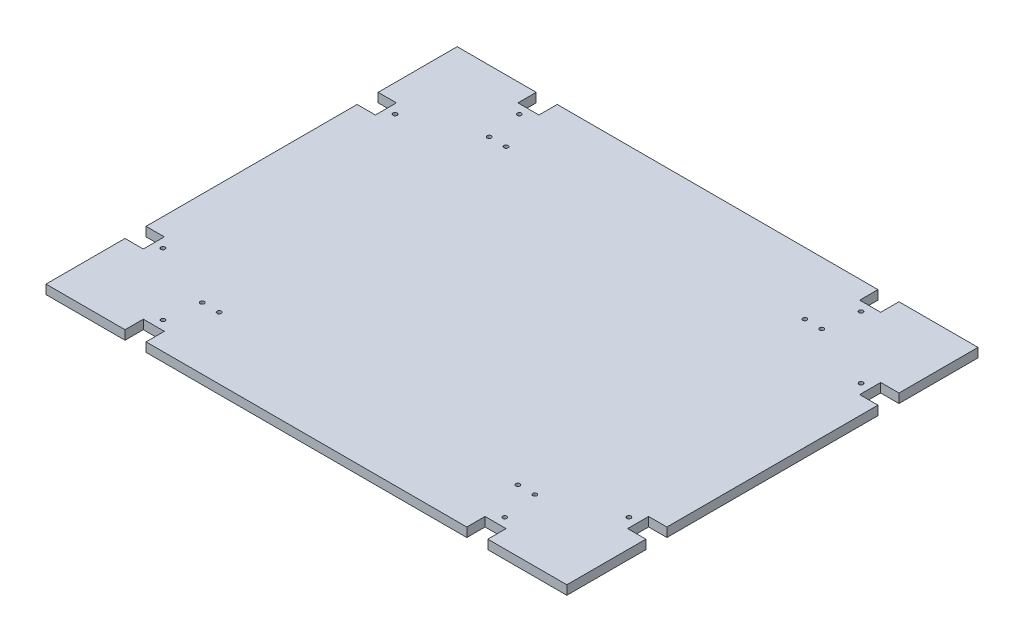
SolidWorks part; units mm, degrees
material "Multistrato di pioppo"
ref_plane "Piano frontale" through (0, 0, 0) normal (0, 0, 1) x (1, 0, 0)
ref_plane "Piano superiore" through (0, 0, 0) normal (0, 1, 0) x (1, 0, 0)
ref_plane "Piano destro" through (0, 0, 0) normal (1, 0, 0) x (0, 0, -1)
sketch "Schizzo1" plane through (0, 0, 0) normal (0, 1, 0) x (1, 0, 0)
  line L1 (0, 0) -> (-570, 0)
  line L2 (0, 0) -> (0, 450)
  line L3 (0, 450) -> (-570, 450)
  line L4 (-570, 0) -> (-570, 450)
  dimension "D1" = 570
  dimension "D2" = 450
extrude "Estrusione-Estrusione1" add sketch "Schizzo1" along normal blind 10
sketch "Schizzo2" plane through (0, 0, 0) normal (0, -1, 0) x (1, 0, 0)
  line L0 (-570, 0) -> (0, 0) construction
  line L1 (-483.5, 0) -> (-460.5, 0)
  line L3 (-483.5, 0) -> (-483.5, -20)
  line L5 (-483.5, -20) -> (-460.5, -20)
  line L6 (-460.5, 0) -> (-460.5, -20)
  line L7 (-483.5, 0) -> (-460.5, -20) construction
  line L8 (-483.5, -20) -> (-460.5, 0) construction
  line L9 (0, 0) -> (0, -450) construction
  line L10 (-109.5, 0) -> (-86.5, 0)
  line L11 (-109.5, 0) -> (-109.5, -20)
  line L12 (-109.5, -20) -> (-86.5, -20)
  line L13 (-86.5, 0) -> (-86.5, -20)
  line L14 (-109.5, 0) -> (-86.5, -20) construction
  line L15 (-109.5, -20) -> (-86.5, 0) construction
  line L16 (0, -86.5) -> (-20, -86.5)
  line L17 (0, -86.5) -> (0, -109.5)
  line L18 (0, -109.5) -> (-20, -109.5)
  line L19 (-20, -86.5) -> (-20, -109.5)
  line L20 (0, -86.5) -> (-20, -109.5) construction
  line L21 (0, -109.5) -> (-20, -86.5) construction
  line L22 (0, -450) -> (-570, -450) construction
  line L23 (0, -340.5) -> (-20, -340.5)
  line L24 (0, -340.5) -> (0, -363.5)
  line L25 (0, -363.5) -> (-20, -363.5)
  line L26 (-20, -340.5) -> (-20, -363.5)
  line L27 (0, -340.5) -> (-20, -363.5) construction
  line L28 (0, -363.5) -> (-20, -340.5) construction
  line L29 (-86.5, -450) -> (-109.5, -450)
  line L30 (-86.5, -450) -> (-86.5, -430)
  line L31 (-86.5, -430) -> (-109.5, -430)
  line L32 (-109.5, -450) -> (-109.5, -430)
  line L33 (-86.5, -450) -> (-109.5, -430) construction
  line L34 (-86.5, -430) -> (-109.5, -450) construction
  line L35 (-570, -450) -> (-570, 0) construction
  line L36 (-460.5, -450) -> (-483.5, -450)
  line L37 (-460.5, -450) -> (-460.5, -430)
  line L38 (-460.5, -430) -> (-483.5, -430)
  line L39 (-483.5, -450) -> (-483.5, -430)
  line L40 (-460.5, -450) -> (-483.5, -430) construction
  line L41 (-460.5, -430) -> (-483.5, -450) construction
  line L42 (-570, -363.5) -> (-550, -363.5)
  line L43 (-570, -363.5) -> (-570, -340.5)
  line L44 (-570, -340.5) -> (-550, -340.5)
  line L45 (-550, -363.5) -> (-550, -340.5)
  line L46 (-570, -363.5) -> (-550, -340.5) construction
  line L47 (-570, -340.5) -> (-550, -363.5) construction
  line L48 (-560, -98) -> (-10, -98) construction
  line L49 (-570, -109.5) -> (-550, -109.5)
  line L50 (-570, -109.5) -> (-570, -86.5)
  line L51 (-570, -86.5) -> (-550, -86.5)
  line L52 (-550, -109.5) -> (-550, -86.5)
  line L53 (-570, -109.5) -> (-550, -86.5) construction
  line L54 (-570, -86.5) -> (-550, -109.5) construction
  line L55 (-472, -10) -> (-472, -440) construction
  line L56 (-98, -440) -> (-98, -10) construction
  line L57 (-560, -352) -> (-10, -352) construction
  circle A2 centre (-467, -68) radius 2.25
  circle A3 centre (-448.5, -68) radius 2.25
  circle A6 centre (-121.5, -68) radius 2.25
  circle A7 centre (-103, -68) radius 2.25
  circle A8 centre (-467, -382) radius 2.25
  circle A9 centre (-448.5, -382) radius 2.25
  circle A14 centre (-121.5, -382) radius 2.25
  circle A15 centre (-103, -382) radius 2.25
  circle A16 centre (-472, -420) radius 2.25
  circle A17 centre (-540, -352) radius 2.25
  circle A18 centre (-540, -98) radius 2.25
  circle A19 centre (-472, -30) radius 2.25
  circle A20 centre (-98, -30) radius 2.25
  circle A21 centre (-30, -98) radius 2.25
  circle A22 centre (-30, -352) radius 2.25
  circle A23 centre (-98, -420) radius 2.25
  point P4 (-472, -10)
  point P17 (-98, -10)
  point P34 (-10, -98)
  point P41 (-10, -352)
  point P52 (-98, -440)
  point P59 (-472, -440)
  point P64 (-560, -352)
  point P71 (-560, -98)
  dimension "D1" = 4.5
  dimension "D3" = 98
  dimension "D5" = 98
  dimension "D2" = 98
  dimension "D4" = 98
  dimension "D6" = 23
  dimension "D7" = 20
extrude "Taglio-Estrusione1" cut sketch "Schizzo2" against normal blind 10
sketch "Schizzo3" plane through (0, 0, 0) normal (0, -1, 0) x (1, 0, 0)
  line L0 (-570, -225) -> (-551.2, -225)
  line L1 (-570, -340.5) -> (-570, -109.5) construction
  line L2 (-551.2, -225) -> (-560.3, -215)
  line L3 (-560.3, -215) -> (-522.7, -215)
  line L4 (-522.7, -215) -> (-531.8, -225)
  line L5 (-531.8, -225) -> (-513, -225)
  line L6 (-551.2, -225) -> (-531.8, -225) construction
  line L7 (-541.5, -225) -> (-541.5, -215) construction
  line L8 (-513, -225) -> (-494.2, -225)
  line L9 (-494.2, -225) -> (-503.3, -215)
  line L10 (-503.3, -215) -> (-465.7, -215)
  line L11 (-465.7, -215) -> (-474.8, -225)
  line L12 (-474.8, -225) -> (-456, -225)
  line L13 (-494.2, -225) -> (-474.8, -225) construction
  line L14 (-484.5, -225) -> (-484.5, -215) construction
  line L15 (-456, -225) -> (-437.2, -225)
  line L16 (-437.2, -225) -> (-446.3, -215)
  line L17 (-446.3, -215) -> (-408.7, -215)
  line L18 (-408.7, -215) -> (-417.8, -225)
  line L19 (-417.8, -225) -> (-399, -225)
  line L20 (-437.2, -225) -> (-417.8, -225) construction
  line L21 (-427.5, -225) -> (-427.5, -215) construction
  line L22 (-399, -225) -> (-380.2, -225)
  line L23 (-380.2, -225) -> (-389.3, -215)
  line L24 (-389.3, -215) -> (-351.7, -215)
  line L25 (-351.7, -215) -> (-360.8, -225)
  line L26 (-360.8, -225) -> (-342, -225)
  line L27 (-380.2, -225) -> (-360.8, -225) construction
  line L28 (-370.5, -225) -> (-370.5, -215) construction
  line L29 (-342, -225) -> (-323.2, -225)
  line L30 (-323.2, -225) -> (-332.3, -215)
  line L31 (-332.3, -215) -> (-294.7, -215)
  line L32 (-294.7, -215) -> (-303.8, -225)
  line L33 (-303.8, -225) -> (-285, -225)
  line L34 (-323.2, -225) -> (-303.8, -225) construction
  line L35 (-313.5, -225) -> (-313.5, -215) construction
  line L36 (-285, -225) -> (-266.2, -225)
  line L37 (-266.2, -225) -> (-275.3, -215)
  line L38 (-275.3, -215) -> (-237.7, -215)
  line L39 (-237.7, -215) -> (-246.8, -225)
  line L40 (-246.8, -225) -> (-228, -225)
  line L41 (-266.2, -225) -> (-246.8, -225) construction
  line L42 (-256.5, -225) -> (-256.5, -215) construction
  line L43 (-228, -225) -> (-209.2, -225)
  line L44 (-209.2, -225) -> (-218.3, -215)
  line L45 (-218.3, -215) -> (-180.7, -215)
  line L46 (-180.7, -215) -> (-189.8, -225)
  line L47 (-189.8, -225) -> (-171, -225)
  line L48 (-209.2, -225) -> (-189.8, -225) construction
  line L49 (-199.5, -225) -> (-199.5, -215) construction
  line L50 (-171, -225) -> (-152.2, -225)
  line L51 (-152.2, -225) -> (-161.3, -215)
  line L52 (-161.3, -215) -> (-123.7, -215)
  line L53 (-123.7, -215) -> (-132.8, -225)
  line L54 (-132.8, -225) -> (-114, -225)
  line L55 (-152.2, -225) -> (-132.8, -225) construction
  line L56 (-142.5, -225) -> (-142.5, -215) construction
  line L57 (-114, -225) -> (-95.2, -225)
  line L58 (-95.2, -225) -> (-104.3, -215)
  line L59 (-104.3, -215) -> (-66.7, -215)
  line L60 (-66.7, -215) -> (-75.8, -225)
  line L61 (-75.8, -225) -> (-57, -225)
  line L62 (-95.2, -225) -> (-75.8, -225) construction
  line L63 (-85.5, -225) -> (-85.5, -215) construction
  line L64 (-57, -225) -> (-38.2, -225)
  line L65 (-38.2, -225) -> (-47.3, -215)
  line L66 (-47.3, -215) -> (-9.7, -215)
  line L67 (-9.7, -215) -> (-18.8, -225)
  line L68 (-18.8, -225) -> (0, -225)
  line L69 (-38.2, -225) -> (-18.8, -225) construction
  line L70 (-28.5, -225) -> (-28.5, -215) construction
  line L71 (0, -109.5) -> (0, -340.5) construction
  dimension "D1" = 57
  dimension "D2" = 10
  dimension "D3" = 37.6
  dimension "D4" = 19.4
  dimension "D5" = 10
